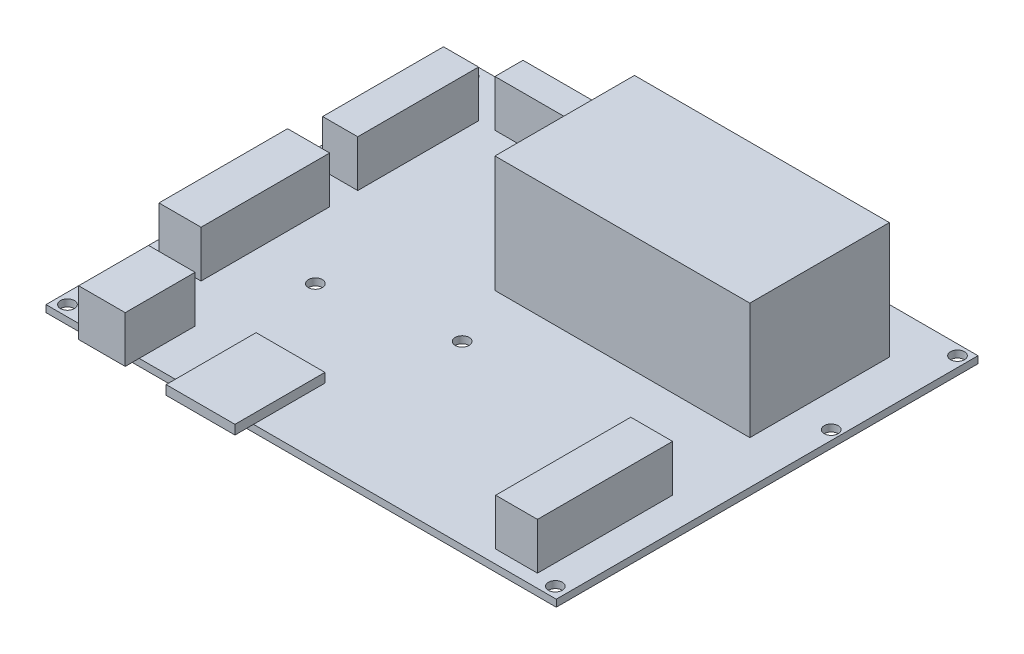
SolidWorks part; units mm, degrees
ref_plane "Front Plane" through (0, 0, 0) normal (0, 0, 1) x (1, 0, 0)
ref_plane "Top Plane" through (0, 0, 0) normal (0, 1, 0) x (1, 0, 0)
ref_plane "Right Plane" through (0, 0, 0) normal (1, 0, 0) x (0, 0, -1)
sketch "Sketch1" plane through (0, 0, 0) normal (0, 1, 0) x (1, 0, 0)
  line L0 (-54.75, 45.25) -> (54.75, -45.25) construction
  line L1 (-54.75, 45.25) -> (54.75, 45.25)
  line L2 (-54.75, 45.25) -> (-54.75, -45.25)
  line L3 (-54.75, -45.25) -> (54.75, -45.25)
  line L4 (54.75, 45.25) -> (54.75, -45.25)
  circle A0 centre (-52.45, -42.95) radius 1.5
  circle A1 centre (-29.75, -12.45) radius 1.5
  circle A2 centre (52.25, -42.95) radius 1.5
  circle A3 centre (52.55, 43.05) radius 1.5
  circle A4 centre (-51.75, 42.55) radius 1.5
  circle A5 centre (-3.25, -7.45) radius 1.5
  circle A6 centre (52.75, 15.75) radius 1.5
  dimension "D3" = 3
  dimension "D4" = 2.3
  dimension "D5" = 2.3
  dimension "D6" = 107
  dimension "D7" = 2.3
  dimension "D9" = 32.8
  dimension "D11" = 37.8
  dimension "D13" = 87.8
  dimension "D15" = 88.3
  dimension "D17" = 61
  dimension "D1" = 90.5
  dimension "D2" = 109.5
  dimension "D8" = 25
  dimension "D10" = 51.5
  dimension "D12" = 3
  dimension "D14" = 107.3
  dimension "D16" = 107.5
extrude "Boss-Extrude1" add sketch "Sketch1" along normal blind 1.5
sketch "Sketch2" plane through (0, 1.5, 0) normal (0, 1, 0) x (1, 0, 0)
  line L0 (-54.75, -45.25) -> (54.75, -45.25) construction
  line L1 (-44.75, -33.25) -> (-34.75, -33.25)
  line L2 (-44.75, -33.25) -> (-44.75, -48.25)
  line L3 (-44.75, -48.25) -> (-34.75, -48.25)
  line L4 (-34.75, -33.25) -> (-34.75, -48.25)
  line L5 (-54.75, 45.25) -> (-54.75, -45.25) construction
  dimension "D1" = 10
  dimension "D2" = 15
  dimension "D3" = 12
  dimension "D4" = 10
extrude "Boss-Extrude2" add sketch "Sketch2" along normal blind 10
sketch "Sketch3" plane through (0, 1.5, 0) normal (0, 1, 0) x (1, 0, 0)
  line L1 (-24.9921, -29.9199) -> (-10.2225, -29.9199)
  line L2 (-24.9921, -29.9199) -> (-24.9921, -49.2293)
  line L3 (-24.9921, -49.2293) -> (-10.2225, -49.2293)
  line L4 (-10.2225, -29.9199) -> (-10.2225, -49.2293)
extrude "Boss-Extrude3" add sketch "Sketch3" along normal blind 2
sketch "Sketch4" plane through (0, 1.5, 0) normal (0, 1, 0) x (1, 0, 0)
  line L1 (-9.2002, 35.4803) -> (45.4992, 35.4803)
  line L2 (-9.2002, 35.4803) -> (-9.2002, 5.5378)
  line L3 (-9.2002, 5.5378) -> (45.4992, 5.5378)
  line L4 (45.4992, 35.4803) -> (45.4992, 5.5378)
extrude "Boss-Extrude4" add sketch "Sketch4" along normal blind 25
sketch "Sketch5" plane through (0, 1.5, 0) normal (0, 1, 0) x (1, 0, 0)
  line L1 (-51.5212, 3.3632) -> (-42.4883, 3.3632)
  line L2 (-51.5212, 3.3632) -> (-51.5212, -24.2374)
  line L3 (-51.5212, -24.2374) -> (-42.4883, -24.2374)
  line L4 (-42.4883, 3.3632) -> (-42.4883, -24.2374)
  line L5 (-50.0157, 35.313) -> (-42.4883, 35.313)
  line L6 (-50.0157, 35.313) -> (-50.0157, 9.3852)
  line L7 (-50.0157, 9.3852) -> (-42.4883, 9.3852)
  line L8 (-42.4883, 35.313) -> (-42.4883, 9.3852)
  line L9 (-38.9754, 41.335) -> (-16.8949, 41.335)
  line L10 (-38.9754, 41.335) -> (-38.9754, 35.313)
  line L11 (-38.9754, 35.313) -> (-16.8949, 35.313)
  line L12 (-16.8949, 41.335) -> (-16.8949, 35.313)
  line L13 (38.9254, -13.4408) -> (47.902, -13.4408)
  line L14 (38.9254, -13.4408) -> (38.9254, -42.4351)
  line L15 (38.9254, -42.4351) -> (47.902, -42.4351)
  line L16 (47.902, -13.4408) -> (47.902, -42.4351)
extrude "Boss-Extrude5" add sketch "Sketch5" along normal blind 10
